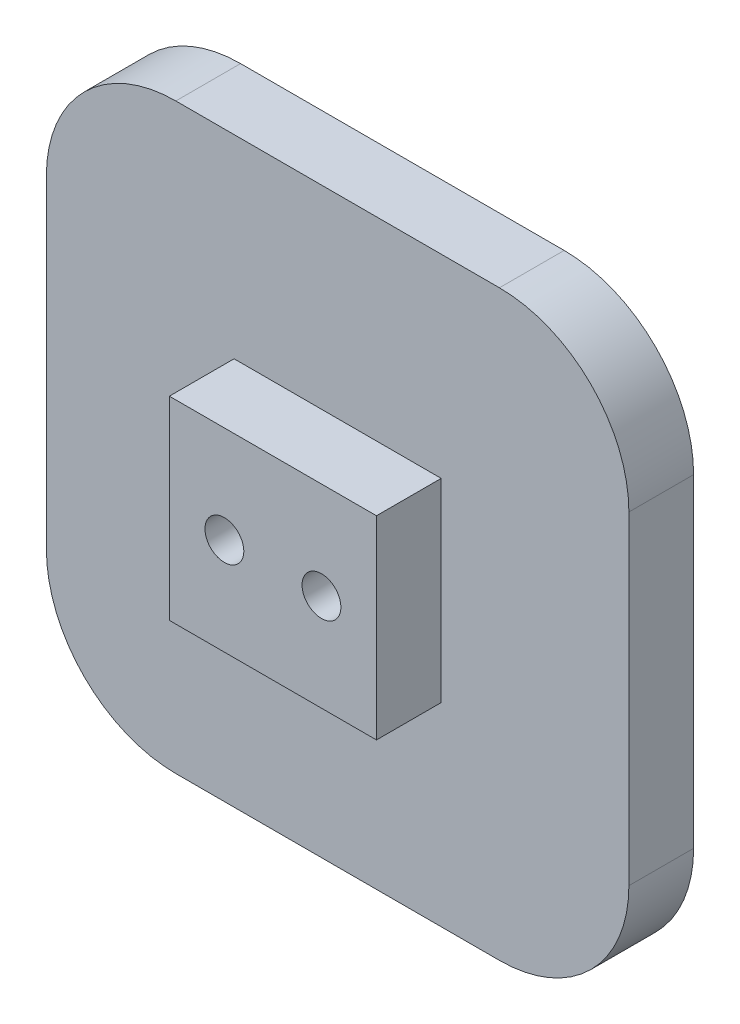
SolidWorks part; units mm, degrees
ref_plane "Ön Düzlem" through (0, 0, 0) normal (0, 0, 1) x (1, 0, 0)
ref_plane "Üst Düzlem" through (0, 0, 0) normal (0, 1, 0) x (1, 0, 0)
ref_plane "Sağ Düzlem" through (0, 0, 0) normal (1, 0, 0) x (0, 0, -1)
sketch "Çizim1" plane through (0, 0, 0) normal (0, 0, 1) x (1, 0, 0)
  line L0 (-41.5414, -1.1109) -> (-41.5414, 48.8891)
  line L1 (-21.5414, 68.8891) -> (28.4586, 68.8891)
  line L2 (-21.5414, -21.1109) -> (28.4586, -21.1109)
  line L3 (48.4586, -1.1109) -> (48.4586, 48.8891)
  arc A0 (-21.5414, 68.8891) -> (-41.5414, 48.8891) centre (-21.5414, 48.8891) ccw
  arc A1 (28.4586, 68.8891) -> (48.4586, 48.8891) centre (28.4586, 48.8891) cw
  arc A2 (28.4586, -21.1109) -> (48.4586, -1.1109) centre (28.4586, -1.1109) ccw
  arc A3 (-21.5414, -21.1109) -> (-41.5414, -1.1109) centre (-21.5414, -1.1109) cw
extrude "Yükseklik-Ekstrüzyon1" add sketch "Çizim1" along normal blind 20
sketch "Sketch1" plane through (0, 0, 0) normal (0, 0, 1) x (1, 0, 0)
  circle A0 centre (-4.0414, 23.8891) radius 2.5
  circle A1 centre (10.9586, 23.8891) radius 2.5
extrude "Cut-Extrude1" cut sketch "Sketch1" along normal blind 44 and the other way blind 10
sketch "Sketch2" plane through (0, 0, 0) normal (0, 0, 1) x (1, 0, 0)
  line L0 (-12.5414, 38.8891) -> (19.4586, 38.8891)
  line L3 (19.4586, 38.8891) -> (19.4586, 68.8891)
  line L4 (28.4586, 68.8891) -> (-21.5414, 68.8891) construction
  line L5 (19.4586, 68.8891) -> (-12.5414, 68.8891)
  line L6 (-12.5414, 68.8891) -> (-12.5414, 38.8891)
extrude "Cut-Extrude3" cut sketch "Sketch2" along normal blind 27
sketch "Sketch3" plane through (0, 0, 0) normal (0, 0, 1) x (1, 0, 0)
  line L1 (-12.5414, 38.8891) -> (19.4586, 38.8891)
  line L2 (-12.5414, 38.8891) -> (-12.5414, 68.8891)
  line L3 (-12.5414, 68.8891) -> (19.4586, 68.8891)
  line L4 (19.4586, 38.8891) -> (19.4586, 68.8891)
extrude "Boss-Extrude1" add sketch "Sketch3" along normal blind 16
sketch "Sketch4" plane through (0, 0, 0) normal (0, 0, 1) x (1, 0, 0)
  line L1 (15.6929, 23.8891) -> (13.3258, 27.9891)
  line L2 (13.3258, 27.9891) -> (8.5915, 27.9891)
  line L3 (8.5915, 27.9891) -> (6.2244, 23.8891)
  line L4 (6.2244, 23.8891) -> (8.5915, 19.7891)
  line L5 (8.5915, 19.7891) -> (13.3258, 19.7891)
  line L6 (13.3258, 19.7891) -> (15.6929, 23.8891)
  line L7 (0.6929, 23.8891) -> (-1.6742, 27.9891)
  line L8 (-1.6742, 27.9891) -> (-6.4085, 27.9891)
  line L9 (-6.4085, 27.9891) -> (-8.7756, 23.8891)
  line L10 (-8.7756, 23.8891) -> (-6.4085, 19.7891)
  line L11 (-6.4085, 19.7891) -> (-1.6742, 19.7891)
  line L12 (-1.6742, 19.7891) -> (0.6929, 23.8891)
  circle A0 centre (10.9586, 23.8891) radius 4.1 construction
  circle A2 centre (-4.0414, 23.8891) radius 4.1 construction
extrude "Cut-Extrude4" cut sketch "Sketch4" along normal blind 4
sketch "Sketch5" plane through (0, 0, 0) normal (0, 0, 1) x (1, 0, 0)
  line L1 (18.9616, 32.8218) -> (-14.5543, 32.8218)
  line L2 (18.9616, 32.8218) -> (18.9616, 14.5135)
  line L3 (18.9616, 14.5135) -> (-14.5543, 14.5135)
  line L4 (-14.5543, 32.8218) -> (-14.5543, 14.5135)
extrude "Boss-Extrude2" add sketch "Sketch5" along normal blind 10
sketch "Sketch6" plane through (0, 0, 0) normal (0, 0, 1) x (1, 0, 0)
  circle A0 centre (-4.0414, 23.8891) radius 2.5
  circle A1 centre (10.9586, 23.8891) radius 2.5
extrude "Cut-Extrude5" cut sketch "Sketch6" against normal blind 25 and the other way blind 53
sketch "Sketch7" plane through (0, 0, 0) normal (0, 0, 1) x (1, 0, 0)
  line L2 (-12.5414, 68.8891) -> (-49.0364, 68.8891)
  line L3 (-12.5414, 68.8891) -> (-12.5414, -22.5963)
  line L4 (-12.5414, -22.5963) -> (-49.0364, -22.5963)
  line L5 (-49.0364, 68.8891) -> (-49.0364, -22.5963)
  line L6 (19.4586, 68.8891) -> (57.7649, 68.8891)
  line L7 (19.4586, 68.8891) -> (19.4586, -22.5963)
  line L8 (19.4586, -22.5963) -> (57.7649, -22.5963)
  line L9 (57.7649, 68.8891) -> (57.7649, -22.5963)
extrude "Cut-Extrude7" cut sketch "Sketch7" along normal blind 30
sketch "Sketch8" plane through (0, 0, 0) normal (0, 0, 1) x (1, 0, 0)
  line L0 (-41.5414, 68.8891) -> (-12.5414, 68.8891)
  line L1 (19.4586, 68.8891) -> (48.4586, 68.8891)
  line L3 (-41.5414, 68.8891) -> (-41.5414, -21.1109)
  line L4 (-41.5414, -21.1109) -> (-12.5414, -21.1109)
  line L5 (-12.5414, 68.8891) -> (-12.5414, -21.1109)
  line L8 (48.4586, 68.8891) -> (48.4586, -21.1109)
  line L9 (48.4586, -21.1109) -> (19.4586, -21.1109)
  line L10 (19.4586, 68.8891) -> (19.4586, -21.1109)
extrude "Boss-Extrude3" add sketch "Sketch8" along normal blind 10
sketch "Sketch9" plane through (0, 0, 0) normal (0, 0, 1) x (1, 0, 0)
  line L0 (-41.5414, 68.8891) -> (-21.5414, 68.8891)
  line L1 (-12.5414, 68.8891) -> (-41.5414, 68.8891) construction
  line L3 (-41.5414, 68.8891) -> (-41.5414, 48.8891)
  line L9 (48.4586, 68.8891) -> (48.4586, 48.8891)
  line L10 (48.4586, 68.8891) -> (28.4586, 68.8891)
  line L11 (48.4586, -21.1109) -> (28.4586, -21.1109)
  line L12 (48.4586, -21.1109) -> (48.4586, -1.1109)
  line L13 (-41.5414, -21.1109) -> (-41.5414, -1.1109)
  line L14 (-41.5414, -21.1109) -> (-21.5414, -21.1109)
  arc A0 (-21.5414, 68.8891) -> (-41.5414, 48.8891) centre (-21.5414, 48.8891) ccw
  arc A1 (28.4586, 68.8891) -> (48.4586, 48.8891) centre (28.4586, 48.8891) cw
  arc A2 (28.4586, -21.1109) -> (48.4586, -1.1109) centre (28.4586, -1.1109) ccw
  arc A3 (-21.5414, -21.1109) -> (-41.5414, -1.1109) centre (-21.5414, -1.1109) cw
extrude "Cut-Extrude8" cut sketch "Sketch9" along normal blind 10
sketch "Sketch10" plane through (0, 0, 0) normal (0, 0, 1) x (1, 0, 0)
  line L0 (19.4586, 38.8891) -> (19.4586, -21.1109) construction
  line L1 (-12.5414, 68.8891) -> (19.4586, 68.8891)
  line L2 (-12.5414, 68.8891) -> (-12.5414, 38.8891)
  line L3 (-12.5414, 38.8891) -> (19.4586, 38.8891)
  line L4 (19.4586, 68.8891) -> (19.4586, 38.8891)
  line L5 (-12.5414, -21.1109) -> (19.4586, -21.1109)
  line L6 (-12.5414, -21.1109) -> (-12.5414, 8.8891)
  line L7 (-12.5414, 8.8891) -> (19.4586, 8.8891)
  line L8 (19.4586, -21.1109) -> (19.4586, 8.8891)
extrude "Cut-Extrude9" cut sketch "Sketch10" along normal blind 28
sketch "Sketch11" plane through (0, 0, 0) normal (0, 0, 1) x (1, 0, 0)
  line L1 (-12.5414, 38.8891) -> (19.4586, 38.8891)
  line L2 (-12.5414, 38.8891) -> (-12.5414, 68.8891)
  line L3 (-12.5414, 68.8891) -> (19.4586, 68.8891)
  line L4 (19.4586, 38.8891) -> (19.4586, 68.8891)
  line L5 (-12.5414, 8.8891) -> (19.4586, 8.8891)
  line L6 (-12.5414, 8.8891) -> (-12.5414, -21.1109)
  line L7 (-12.5414, -21.1109) -> (19.4586, -21.1109)
  line L8 (19.4586, 8.8891) -> (19.4586, -21.1109)
extrude "Boss-Extrude4" add sketch "Sketch11" along normal blind 10
sketch "Sketch12" plane through (0, 0, 0) normal (0, 0, 1) x (1, 0, 0)
  circle A0 centre (-4.0414, 23.8891) radius 3
  circle A1 centre (10.9586, 23.8891) radius 3
extrude "Cut-Extrude10" cut sketch "Sketch12" along normal blind 22
sketch "Sketch13" plane through (0, 0, 0) normal (0, 0, 1) x (1, 0, 0)
  circle A0 centre (10.9586, 23.8891) radius 6
  circle A1 centre (-4.0414, 23.8891) radius 6
extrude "Cut-Extrude11" cut sketch "Sketch13" along normal blind 5
